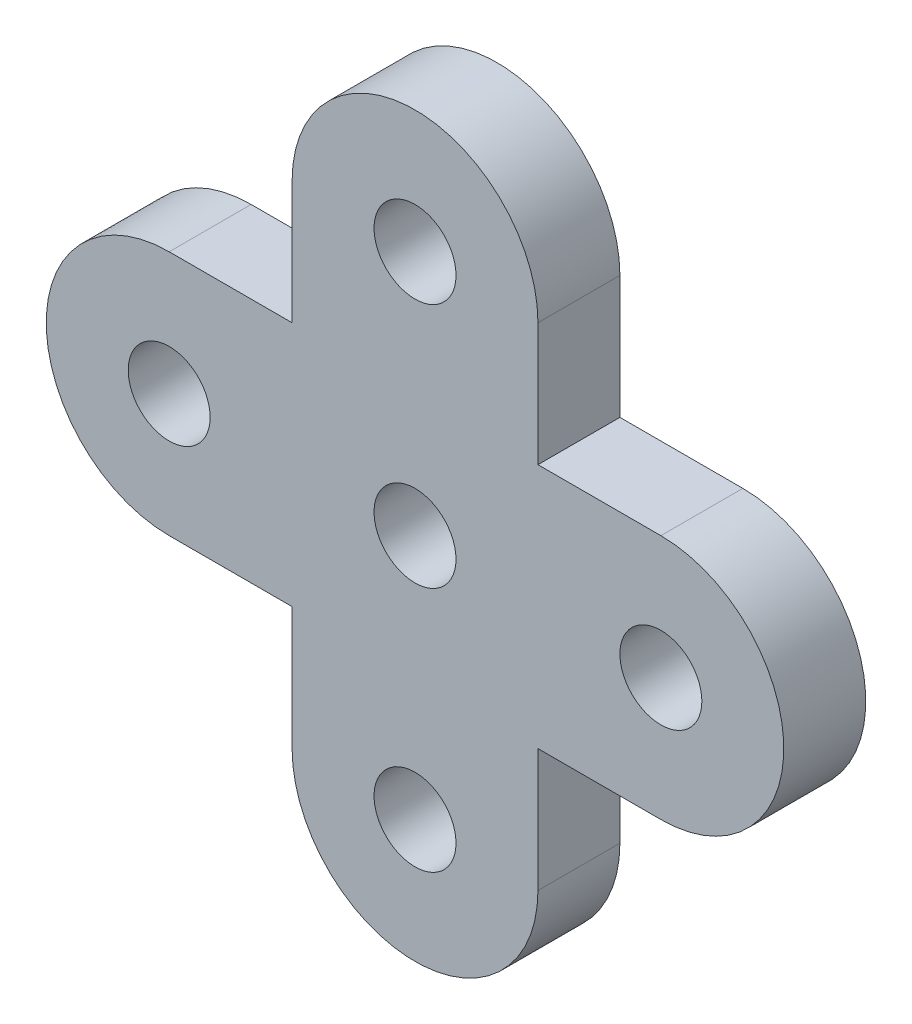
SolidWorks part; units mm, degrees
ref_plane "Alzado" through (0, 0, 0) normal (0, 0, 1) x (1, 0, 0)
ref_plane "Planta" through (0, 0, 0) normal (0, 1, 0) x (1, 0, 0)
ref_plane "Vista lateral" through (0, 0, 0) normal (1, 0, 0) x (0, 0, -1)
sketch "Model" plane through (0, 0, 0) normal (0, 0, 1) x (1, 0, 0)
  line L0 (213.2508, 165.9285) -> (213.2508, 170.4285)
  line L1 (204.2508, 170.4285) -> (204.2508, 165.9285)
  line L2 (217.7508, 165.9285) -> (213.2508, 165.9285)
  line L3 (213.2508, 156.9285) -> (217.7508, 156.9285)
  line L4 (213.2508, 152.4285) -> (213.2508, 156.9285)
  line L5 (204.2508, 165.9285) -> (199.7508, 165.9285)
  line L6 (204.2508, 156.9285) -> (204.2508, 152.4285)
  line L7 (199.7508, 156.9285) -> (204.2508, 156.9285)
  circle A0 centre (208.7508, 152.4285) radius 1.5
  circle A1 centre (208.7508, 161.4285) radius 1.5
  circle A2 centre (208.7508, 170.4285) radius 1.5
  arc A3 (204.2508, 152.4285) -> (213.2508, 152.4285) centre (208.7508, 152.4285) ccw
  arc A4 (213.2508, 170.4285) -> (204.2508, 170.4285) centre (208.7508, 170.4285) ccw
  circle A5 centre (199.7508, 161.4285) radius 1.5
  circle A6 centre (217.7508, 161.4285) radius 1.5
  arc A7 (217.7508, 156.9285) -> (217.7508, 165.9285) centre (217.7508, 161.4285) ccw
  arc A8 (199.7508, 165.9285) -> (199.7508, 156.9285) centre (199.7508, 161.4285) ccw
extrude "Saliente-Extruir1" add sketch "Model" along normal blind 3
